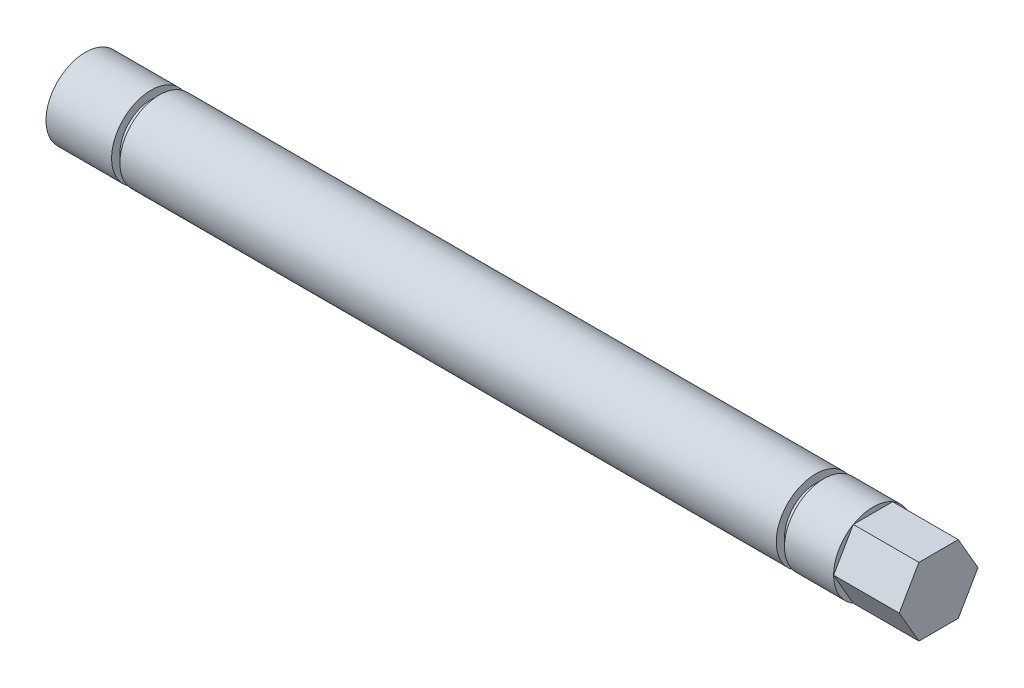
SolidWorks part; units mm, degrees
material "Chrome Stainless Steel"
ref_plane "Front Plane" through (0, 0, 0) normal (0, 0, 1) x (1, 0, 0)
ref_plane "Top Plane" through (0, 0, 0) normal (0, 1, 0) x (1, 0, 0)
ref_plane "Right Plane" through (0, 0, 0) normal (1, 0, 0) x (0, 0, -1)
sketch "Base Sketch" plane through (0, 0, 0) normal (1, 0, 0) x (0, 0, -1)
  circle A0 centre (0, 0) radius 7.62
  dimension "D1" = 15.24
extrude "Base Extrude" add sketch "Base Sketch" along normal blind 165.1
sketch "End Cut Sketch" plane through (0, 0, 0) normal (0, 0, 1) x (1, 0, 0)
  line L0 (13.5001, 7.62) -> (13.5001, -7.62) construction
  line L1 (165.1, 7.62) -> (0, 7.62) construction
  line L2 (0, -7.62) -> (165.1, -7.62) construction
  line L3 (0, 7.62) -> (0, -7.62) construction
  line L4 (14.3002, 6.0198) -> (12.7, 6.0198)
  line L5 (14.3002, 6.0198) -> (14.3002, 9.2202)
  line L6 (14.3002, 9.2202) -> (12.7, 9.2202)
  line L7 (12.7, 6.0198) -> (12.7, 9.2202)
  line L8 (14.3002, 6.0198) -> (12.7, 9.2202) construction
  line L9 (14.3002, 9.2202) -> (12.7, 6.0198) construction
  line L10 (0, 0) -> (165.1, 0) construction
  line L11 (165.1, -7.62) -> (165.1, 7.62) construction
  dimension "D1" = 1.6002
  dimension "D2" = 3.2004
  dimension "D3" = 12.7
revolve "End Cut Revolve" cut sketch "End Cut Sketch" angle 360 about L10
ref_plane "Offset Plane" through (141.3002, 0, 0) normal (-1, 0, 0) x (0, 0, 1)
sketch "Groove Sketch" plane through (141.3002, 0, 0) normal (-1, 0, 0) x (0, 0, 1)
  circle A0 centre (0, 0) radius 6.0198 construction
  circle A1 centre (0, 0) radius 7.62 construction
  circle A2 centre (0, 0) radius 6.0198
  circle A3 centre (0, 0) radius 7.62
extrude "Offset Groove" cut sketch "Groove Sketch" against normal blind 1.6002
sketch "Hexagonal Sketch" plane through (165.1, 0, 0) normal (1, 0, 0) x (0, 0, -1)
  line L1 (-3.81, 6.5991) -> (-7.62, 0)
  line L2 (-7.62, 0) -> (-3.81, -6.5991)
  line L3 (-3.81, -6.5991) -> (3.81, -6.5991)
  line L4 (3.81, -6.5991) -> (7.62, 0)
  line L5 (7.62, 0) -> (3.81, 6.5991)
  line L6 (3.81, 6.5991) -> (-3.81, 6.5991)
  circle A0 centre (0, 0) radius 7.62 construction
  circle A1 centre (0, 0) radius 7.62 construction
extrude "Hexgonal Cut" cut sketch "Hexagonal Sketch" against normal blind 12.7 flip side to cut
